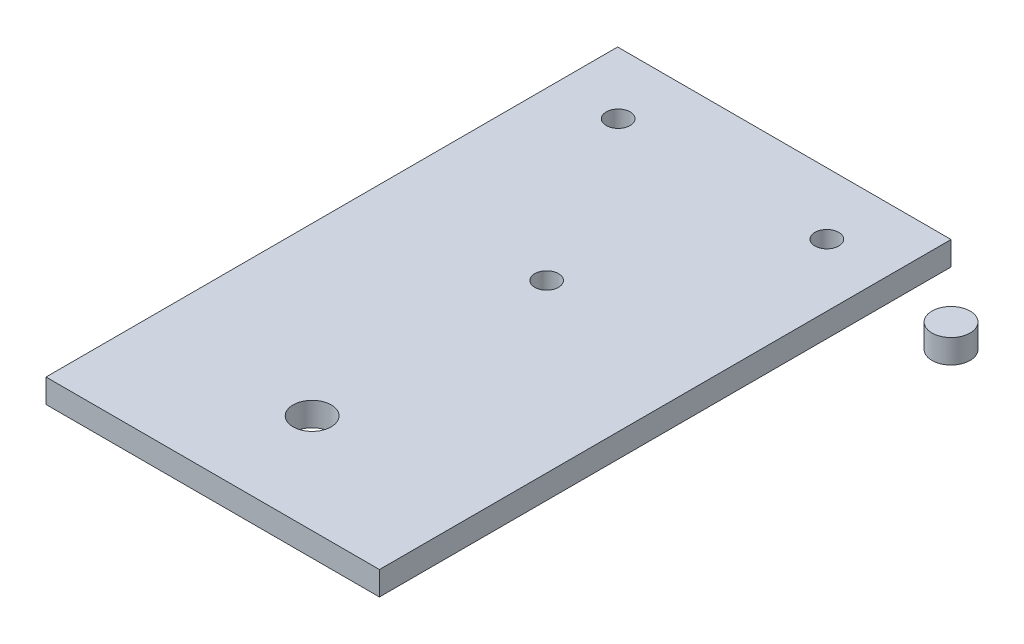
SolidWorks part; units mm, degrees
ref_plane "Front Plane" through (0, 0, 0) normal (0, 0, 1) x (1, 0, 0)
ref_plane "Top Plane" through (0, 0, 0) normal (0, 1, 0) x (1, 0, 0)
ref_plane "Right Plane" through (0, 0, 0) normal (1, 0, 0) x (0, 0, -1)
sketch "Sketch1" plane through (0, 0, 0) normal (0, 1, 0) x (1, 0, 0)
  line L0 (35, 2.946) -> (35, -117.054) construction
  line L1 (0, 2.946) -> (70, 2.946)
  line L2 (0, 2.946) -> (0, -117.054)
  line L3 (0, -117.054) -> (70, -117.054)
  line L4 (70, 2.946) -> (70, -117.054)
  line L5 (35, -117.054) -> (0, -57.054) construction
  line L6 (0, -57.054) -> (70, -57.054) construction
  circle A1 centre (85, -12.054) radius 4
  circle A8 centre (13.0978, -10.0346) radius 2.5
  circle A9 centre (56.9022, -10.0346) radius 2.5
  circle A10 centre (35, -46.9573) radius 2.5
  circle A11 centre (35, -96.1822) radius 4
  dimension "D3" = 8
  dimension "D4" = 8
  dimension "D5" = 5
  dimension "D6" = 5
  dimension "D1" = 70
  dimension "D2" = 120
extrude "Boss-Extrude1" add sketch "Sketch1" along normal blind 5
